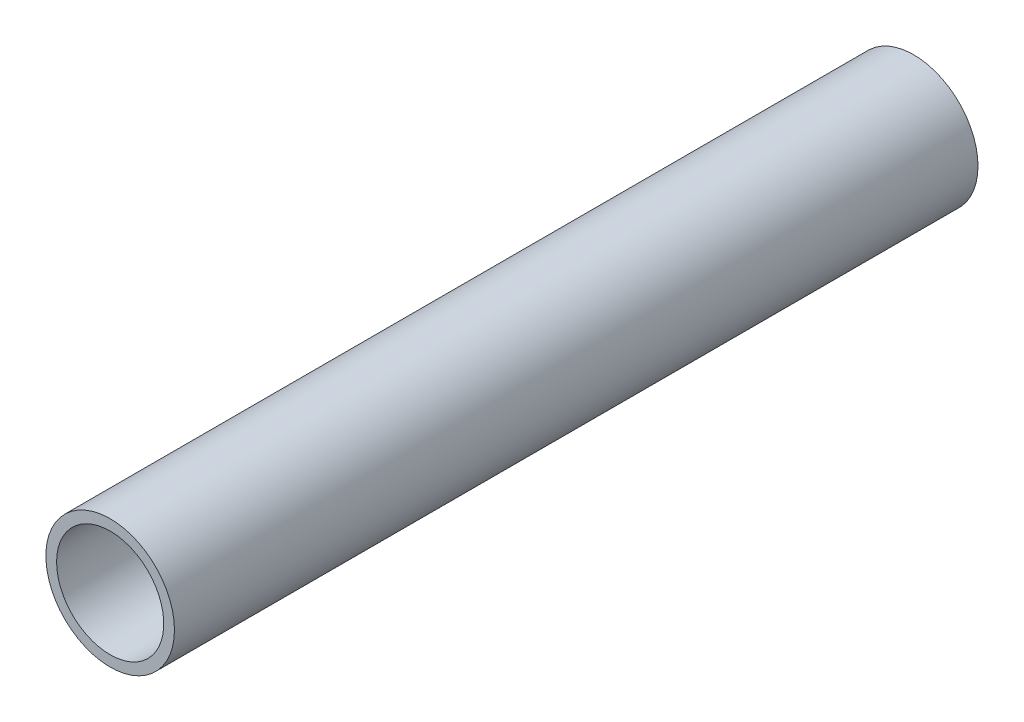
SolidWorks part; units mm, degrees
ref_plane "Front Plane" through (0, 0, 0) normal (0, 0, 1) x (1, 0, 0)
ref_plane "Top Plane" through (0, 0, 0) normal (0, 1, 0) x (1, 0, 0)
ref_plane "Right Plane" through (0, 0, 0) normal (1, 0, 0) x (0, 0, -1)
sketch "Sketch1" plane through (0, 0, 0) normal (0, 0, 1) x (1, 0, 0)
  circle A0 centre (0, 0) radius 12
extrude "Boss-Extrude1" add sketch "Sketch1" along normal blind 150 contours A0
sketch "Sketch2" plane through (0, 0, 0) normal (0, 0, -1) x (-1, 0, 0)
  circle A0 centre (0, 0) radius 10
  dimension "D1" = 20
extrude "Cut-Extrude1" cut sketch "Sketch2" against normal blind 150
